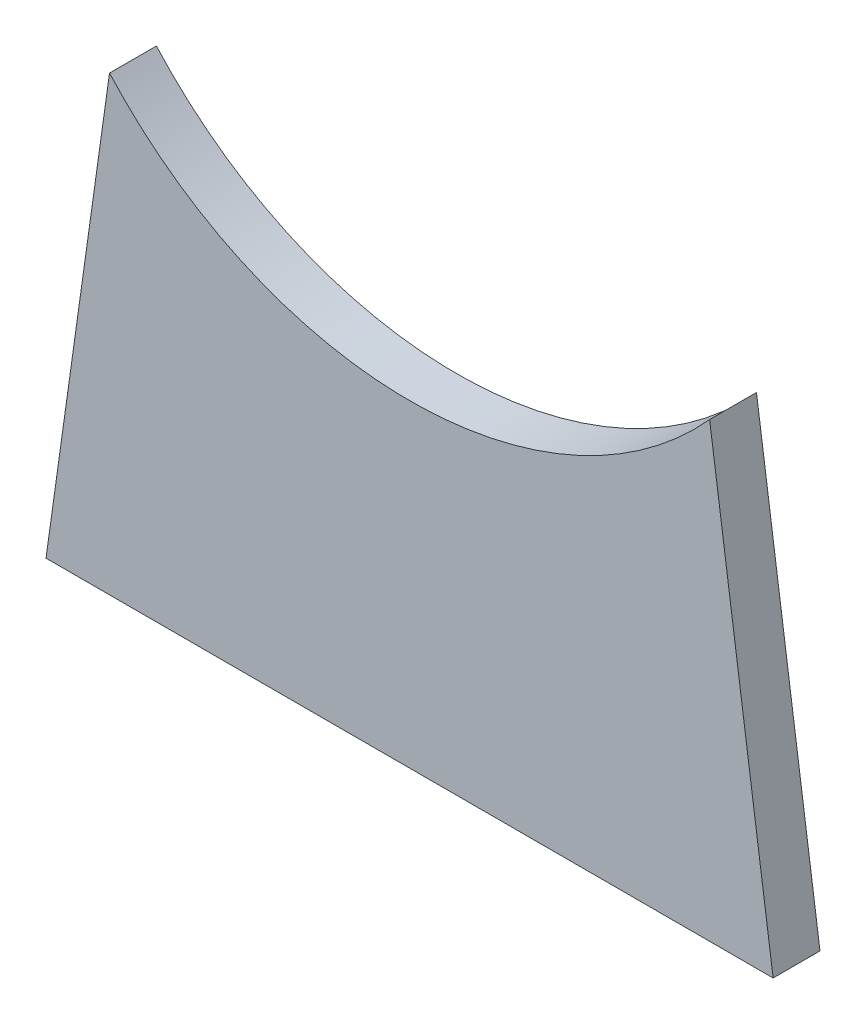
SolidWorks part; units mm, degrees
ref_plane "Front Plane" through (0, 0, 0) normal (0, 0, 1) x (1, 0, 0)
ref_plane "Top Plane" through (0, 0, 0) normal (0, 1, 0) x (1, 0, 0)
ref_plane "Right Plane" through (0, 0, 0) normal (1, 0, 0) x (0, 0, -1)
sketch "Sketch1" plane through (0, 0, 0) normal (0, 0, 1) x (1, 0, 0)
  line L0 (0, 3927.4944) -> (0, 0) construction
  line L1 (-1978.1275, 0) -> (1978.1275, 0)
  line L2 (1978.1275, 0) -> (1632.5727, 2458.75)
  line L3 (-1978.1275, 0) -> (-1632.5727, 2458.75)
  arc A0 (-1632.5727, 2458.75) -> (1632.5727, 2458.75) centre (0, 3927.4944) ccw
  dimension "D1" = 82
  dimension "D4" = 2196.02
  dimension "D2" = 3956.255
  dimension "D3" = 2458.75
extrude "Boss-Extrude1" add sketch "Sketch1" along normal mid plane 255
